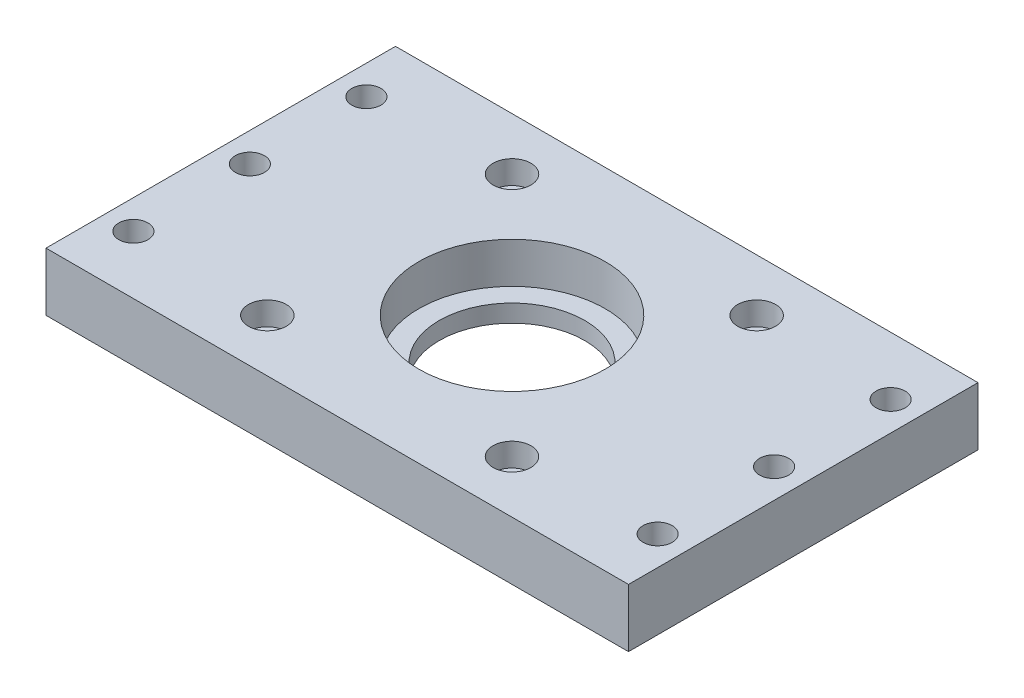
SolidWorks part; units mm, degrees
ref_plane "Alzado" through (0, 0, 0) normal (0, 0, 1) x (1, 0, 0)
ref_plane "Planta" through (0, 0, 0) normal (0, 1, 0) x (1, 0, 0)
ref_plane "Vista lateral" through (0, 0, 0) normal (1, 0, 0) x (0, 0, -1)
sketch "Sketch1" plane through (0, 0, 0) normal (0, 1, 0) x (1, 0, 0)
  line L1 (-50, 30) -> (50, 30)
  line L2 (-50, 30) -> (-50, -30)
  line L3 (-50, -30) -> (50, -30)
  line L4 (50, 30) -> (50, -30)
  line L5 (-50, 30) -> (50, -30) construction
  line L6 (-50, -30) -> (50, 30) construction
  point P0 (0, 0)
  dimension "D1" = 60
  dimension "D2" = 100
extrude "Boss-Extrude1" add sketch "Sketch1" along normal blind 10
sketch "Sketch2" plane through (0, 10, 0) normal (0, 1, 0) x (1, 0, 0)
  line L0 (-50, 0) -> (-45, 0) construction
  line L1 (-50, 30) -> (-50, -30) construction
  line L2 (-45, 0) -> (-45, 20) construction
  line L3 (-45, 0) -> (-45, -20) construction
  circle A0 centre (-45, -20) radius 2.5
  circle A1 centre (-45, 0) radius 2.5
  circle A2 centre (-45, 20) radius 2.5
  dimension "D1" = 5
  dimension "D2" = 5
  dimension "D3" = 20
extrude "Cut-Extrude1" cut sketch "Sketch2" against normal through all
mirror "Mirror1" about plane through (0, 0, 0) normal (1, 0, 0) of "Cut-Extrude1"
sketch "Sketch3" plane through (0, 10, 0) normal (0, 1, 0) x (1, 0, 0)
  circle A0 centre (0, 0) radius 16
  dimension "D1" = 32
extrude "Cut-Extrude2" cut sketch "Sketch3" against normal blind 7
sketch "Sketch4" plane through (0, 3, 0) normal (0, 1, 0) x (1, 0, 0)
  circle A0 centre (0, 0) radius 12.5
  dimension "D1" = 25
extrude "Cut-Extrude3" cut sketch "Sketch4" against normal through all
sketch "Sketch5" plane through (0, 10, 0) normal (0, 1, 0) x (1, 0, 0)
  line L1 (-21, -21) -> (21, -21) construction
  line L2 (-21, -21) -> (-21, 21) construction
  line L3 (-21, 21) -> (21, 21) construction
  line L4 (21, -21) -> (21, 21) construction
  line L5 (-21, -21) -> (21, 21) construction
  line L6 (-21, 21) -> (21, -21) construction
  circle A0 centre (-21, 21) radius 1.5
  point P0 (0, 0)
  dimension "D2" = 3
  dimension "D1" = 42
extrude "Cut-Extrude4" cut sketch "Sketch5" against normal through all
sketch "Sketch6" plane through (0, 10, 0) normal (0, 1, 0) x (1, 0, 0)
  circle A0 centre (-21, 21) radius 3.25
  dimension "D1" = 6.5
extrude "Cut-Extrude5" cut sketch "Sketch6" against normal blind 4
pattern_circular "CirPattern1" count 4 over 360 about axis through (0, 0, 0) along (0, 1, 0) of "Cut-Extrude5", "Cut-Extrude4"
